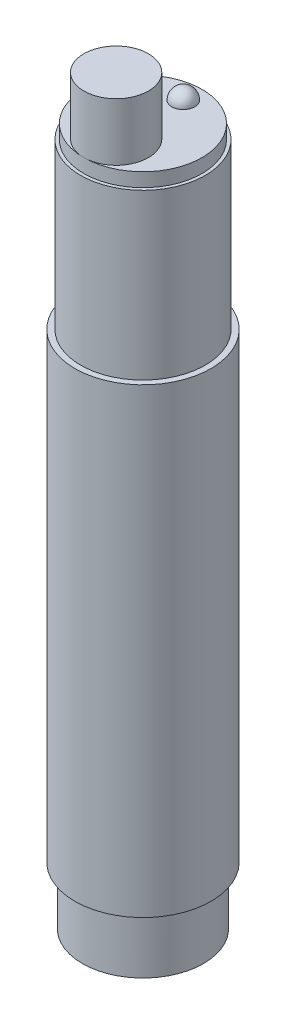
SolidWorks part; units mm, degrees
ref_plane "Alzado" through (0, 0, 0) normal (0, 0, 1) x (1, 0, 0)
ref_plane "Planta" through (0, 0, 0) normal (0, 1, 0) x (1, 0, 0)
ref_plane "Vista lateral" through (0, 0, 0) normal (1, 0, 0) x (0, 0, -1)
sketch "Croquis1" plane through (0, 0, 0) normal (0, 1, 0) x (1, 0, 0)
  circle A0 centre (0, 0) radius 5.9
  dimension "D1" = 11.8
extrude "Saliente-Extruir1" add sketch "Croquis1" along normal blind 40
cosmetic thread "Rosca cosmética1" parameters "D2"=8.344
sketch "Croquis2" plane through (0, 40, 0) normal (0, 1, 0) x (1, 0, 0)
  circle A0 centre (0, 0) radius 5.4
  dimension "D1" = 10.8
extrude "Saliente-Extruir2" add sketch "Croquis2" along normal blind 14.25
sketch "Croquis3" plane through (0, 54.25, 0) normal (0, 1, 0) x (1, 0, 0)
  circle A0 centre (0, 0) radius 5.125
  dimension "D1" = 10.25
extrude "Saliente-Extruir3" add sketch "Croquis3" along normal blind 1.2
sketch "Croquis4" plane through (0, 55.45, 0) normal (0, 1, 0) x (1, 0, 0)
  circle A0 centre (0, -2.325) radius 2.8
  circle A1 centre (0, 0) radius 5.125 construction
  point P4 (0, 0)
  dimension "D1" = 5.6
extrude "Saliente-Extruir4" add sketch "Croquis4" along normal blind 5
sketch "Croquis6" plane through (0, 0, 0) normal (0, -1, 0) x (1, 0, 0)
  circle A0 centre (0, 0) radius 5.25
  dimension "D1" = 10.5
extrude "Saliente-Extruir6" add sketch "Croquis6" along normal blind 5
sketch "Croquis7" plane through (0, 55.45, 0) normal (0, 1, 0) x (1, 0, 0)
  line L0 (0, 2.5) -> (0, 4.5)
  arc A0 (0, 2.5) -> (0, 4.5) centre (0, 3.5) cw
  point P5 (0, 0)
  dimension "D1" = 1
  dimension "D2" = 3.5
revolve "Revolución1" add sketch "Croquis7" angle 360 about L0
